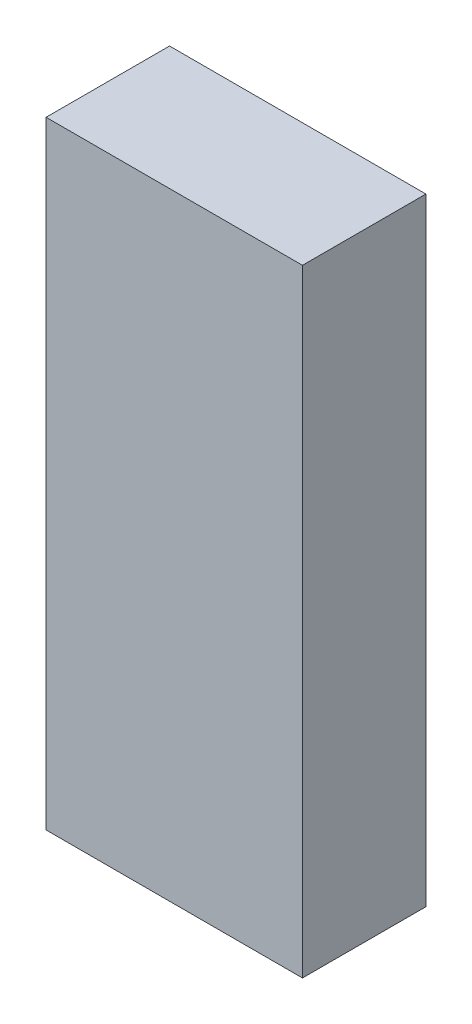
SolidWorks part; units mm, degrees
ref_plane "Plan de face" through (0, 0, 0) normal (0, 0, 1) x (1, 0, 0)
ref_plane "Plan de dessus" through (0, 0, 0) normal (0, 1, 0) x (1, 0, 0)
ref_plane "Plan de droite" through (0, 0, 0) normal (1, 0, 0) x (0, 0, -1)
sketch "Esquisse1" plane through (0, 0, 0) normal (0, 0, 1) x (1, 0, 0)
  line L1 (0, 0) -> (-27, 0)
  line L2 (0, 0) -> (0, 65)
  line L3 (0, 65) -> (-27, 65)
  line L4 (-27, 0) -> (-27, 65)
  point P7 (0, 0)
  point P8 (0, 0)
  dimension "D1" = 65
  dimension "D2" = 27
extrude "Boss.-Extru.1" add sketch "Esquisse1" along normal blind 13
